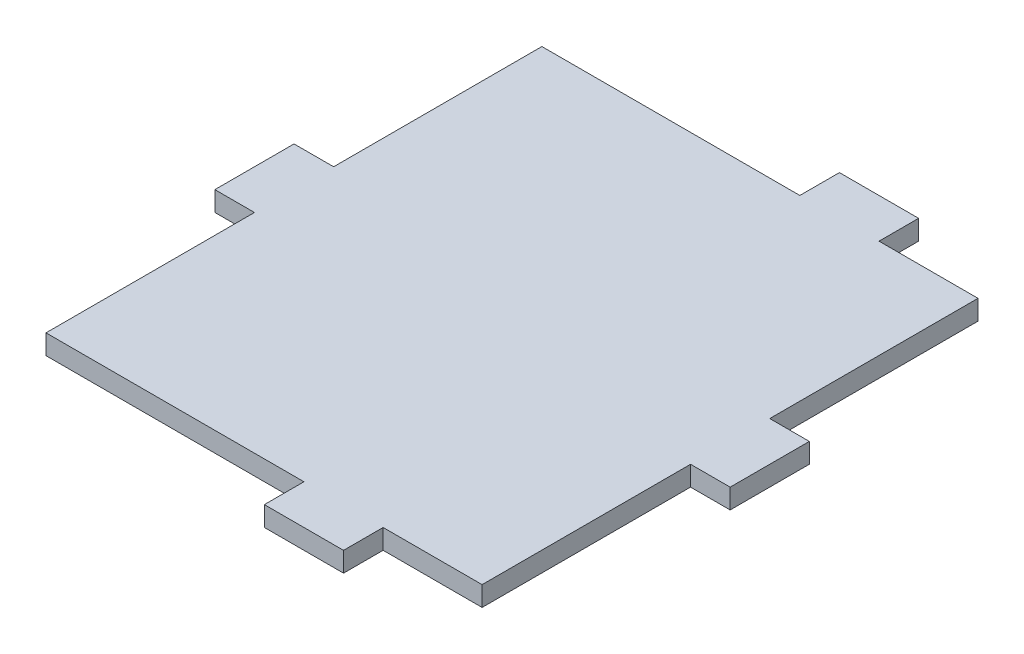
SolidWorks part; units mm, degrees
ref_plane "Front Plane" through (0, 0, 0) normal (0, 0, 1) x (1, 0, 0)
ref_plane "Top Plane" through (0, 0, 0) normal (0, 1, 0) x (1, 0, 0)
ref_plane "Right Plane" through (0, 0, 0) normal (1, 0, 0) x (0, 0, -1)
sketch "Sketch1" plane through (0, 0, 0) normal (0, 1, 0) x (1, 0, 0)
  line L5 (26.03, 12.53) -> (24.03, 12.53)
  line L7 (24.03, 16.53) -> (26.03, 16.53)
  line L8 (26.03, 16.53) -> (26.03, 12.53)
  line L11 (0, 12.53) -> (2, 12.53)
  line L13 (2, 16.53) -> (0, 16.53)
  line L14 (0, 16.53) -> (0, 12.53)
  line L18 (24.03, 16.53) -> (24.03, 27.05)
  line L19 (19.03, 29.05) -> (19.03, 27.05)
  line L21 (15.03, 27.05) -> (15.03, 29.05)
  line L22 (15.03, 29.05) -> (19.03, 29.05)
  line L23 (15.03, 27.05) -> (2, 27.05)
  line L24 (19.03, 27.05) -> (24.03, 27.05)
  line L25 (2, 16.53) -> (2, 27.05)
  line L26 (2, 2) -> (2, 12.53)
  line L27 (19.03, 0) -> (19.03, 2)
  line L29 (15.03, 2) -> (15.03, 0)
  line L30 (15.03, 0) -> (19.03, 0)
  line L31 (19.03, 2) -> (24.03, 2)
  line L32 (15.03, 2) -> (2, 2)
  line L33 (24.03, 2) -> (24.03, 12.53)
extrude "Boss-Extrude1" add sketch "Sketch1" along normal blind 1
